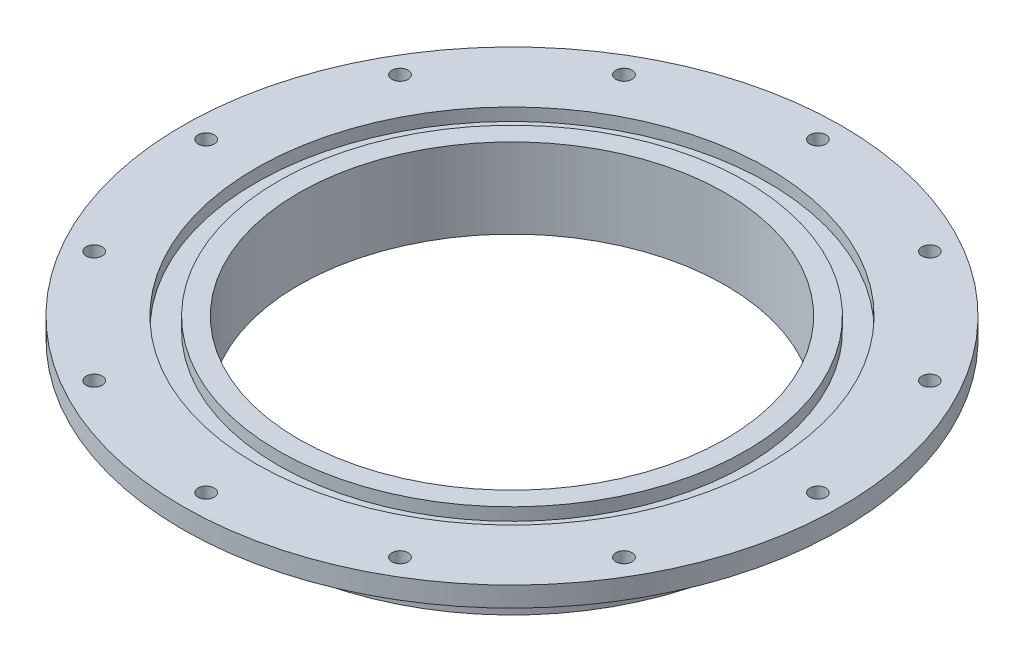
SolidWorks part; units mm, degrees
material "6061-T4 (SS)"
ref_plane "Front Plane" through (0, 0, 0) normal (0, 0, 1) x (1, 0, 0)
ref_plane "Top Plane" through (0, 0, 0) normal (0, 1, 0) x (1, 0, 0)
ref_plane "Right Plane" through (0, 0, 0) normal (1, 0, 0) x (0, 0, -1)
sketch "Sketch1" plane through (0, 0, 0) normal (0, 1, 0) x (1, 0, 0)
  circle A0 centre (0, 0) radius 80.518
  circle A1 centre (0, 0) radius 67.818
  dimension "D1" = 161.036
  dimension "D2" = 12.7
extrude "Inner Cylinder" add sketch "Sketch1" along normal blind 19.05
sketch "Sketch2" plane through (0, 19.05, 0) normal (0, 1, 0) x (1, 0, 0)
  circle A0 centre (0, 0) radius 67.818
  circle A1 centre (0, 0) radius 67.818 construction
  circle A2 centre (0, 0) radius 104.775
  dimension "D1" = 209.55
extrude "Flange" add sketch "Sketch2" along normal blind 6.35
sketch "Sketch4" plane through (0, 25.4, 0) normal (0, 1, 0) x (1, 0, 0)
  line L0 (0, 75.8825) -> (0, 81.2165) construction
  circle A3 centre (0, 0) radius 81.407
  circle A4 centre (0, 0) radius 74.295
  point P7 (0, 78.5495)
  dimension "D1" = 148.59
  dimension "D2" = 7.112
  dimension "D3" = 2.667
extrude "Groove" cut sketch "Sketch4" against normal blind 3.9878
sketch "Sketch5" plane through (0, 25.4, 0) normal (0, 1, 0) x (1, 0, 0)
  line L0 (89.7255, 0) -> (104.775, 0) construction
  circle A0 centre (0, 0) radius 97.2503 construction
  circle A1 centre (0, -97.2503) radius 3.175 construction
  circle A3 centre (0, -97.2503) radius 2.5527
  circle A6 centre (0, 0) radius 89.7255 construction
  circle A7 centre (0, 0) radius 104.775 construction
  point P9 (97.2503, 0)
  dimension "D1" = 5.1054
  dimension "D2" = 179.451
  dimension "D3" = 6.35
extrude "10-32 Clearance Hole" cut sketch "Sketch5" against normal up to surface (6.35 mm away) up to face at (0, 19.05, 80.518)
pattern_circular "CirPattern1" count 12 over 360 about axis through (0, 0, 0) along (0, 1, 0) of "10-32 Clearance Hole"
sketch "Acrylic Tube OD" plane through (0, 25.4, 0) normal (0, 1, 0) x (1, 0, 0)
  circle A0 centre (0, 0) radius 89.7255
  dimension "D1" = 179.451
